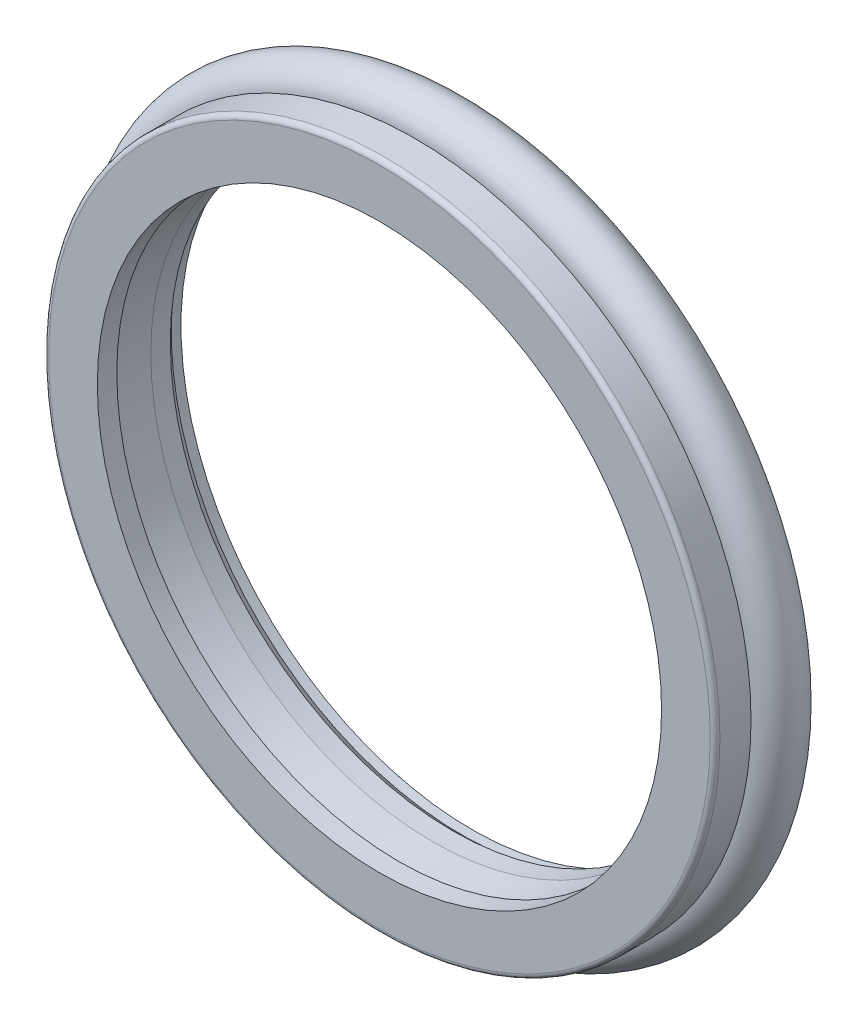
SolidWorks part; units mm, degrees
material "PTFE+NBR"
ref_plane "Front Plane" through (0, 0, 0) normal (0, 0, 1) x (1, 0, 0)
ref_plane "Top Plane" through (0, 0, 0) normal (0, 1, 0) x (1, 0, 0)
ref_plane "Right Plane" through (0, 0, 0) normal (1, 0, 0) x (0, 0, -1)
sketch "Sketch1" plane through (0, 0, 0) normal (1, 0, 0) x (0, 0, -1)
  line L0 (0, 0) -> (11.2675, 0) construction
  line L1 (0.25, 17.25) -> (1.85, 17.25)
  line L2 (0, 17) -> (0, 14.5)
  line L3 (4.75, 15.75) -> (4.75, 14.95)
  line L4 (4.75, 14.95) -> (4.25, 14.95)
  line L5 (4.25, 14.95) -> (3.75, 14.5)
  line L6 (1, 14.7) -> (2.75, 14.5)
  line L7 (4.75, 15.75) -> (1.85, 15.75)
  line L8 (1.85, 15.75) -> (1.85, 17.25)
  line L9 (1, 14.7) -> (1, 14.5)
  line L10 (1, 14.5) -> (0, 14.5)
  line L11 (3.75, 14.5) -> (2.75, 14.5)
  arc A2 (0.25, 17.25) -> (0, 17) centre (0.25, 17) ccw
  circle A4 centre (3.3, 17.05) radius 1.3 construction
  point P4 (0, 0)
  point P5 (3.123, 17.1)
  point P7 (3.529, 17.1)
  point P8 (3.3, 15.75)
  dimension "D8" = 1
  dimension "D12" = 36.7
  dimension "D13" = 2.6
  dimension "D14" = 31.5
  dimension "D16" = 2.9
  dimension "D17" = 0.25
  dimension "D1" = 0.5
  dimension "D2" = 1
  dimension "D3" = 4.75
  dimension "D4" = 1
  dimension "D5" = 34.5
  dimension "D6" = 29
  dimension "D7" = 0.8
  dimension "D9" = 29
  dimension "D10" = 0.2
revolve "Revolve1" add sketch "Sketch1" angle 360 about L0
sketch "Sketch2" plane through (0, 0, 0) normal (1, 0, 0) x (0, 0, -1)
  line L2 (0, 0) -> (10.3771, 0) construction
  circle A0 centre (3.3, 17.05) radius 1.3
  point P9 (2, 18.4953)
  point P10 (2, 18.5629)
  point P11 (3.3, 17.1)
  dimension "D1" = 2.6
  dimension "D2" = 36.7
revolve "Revolve2" add sketch "Sketch2" angle 360 about L2
